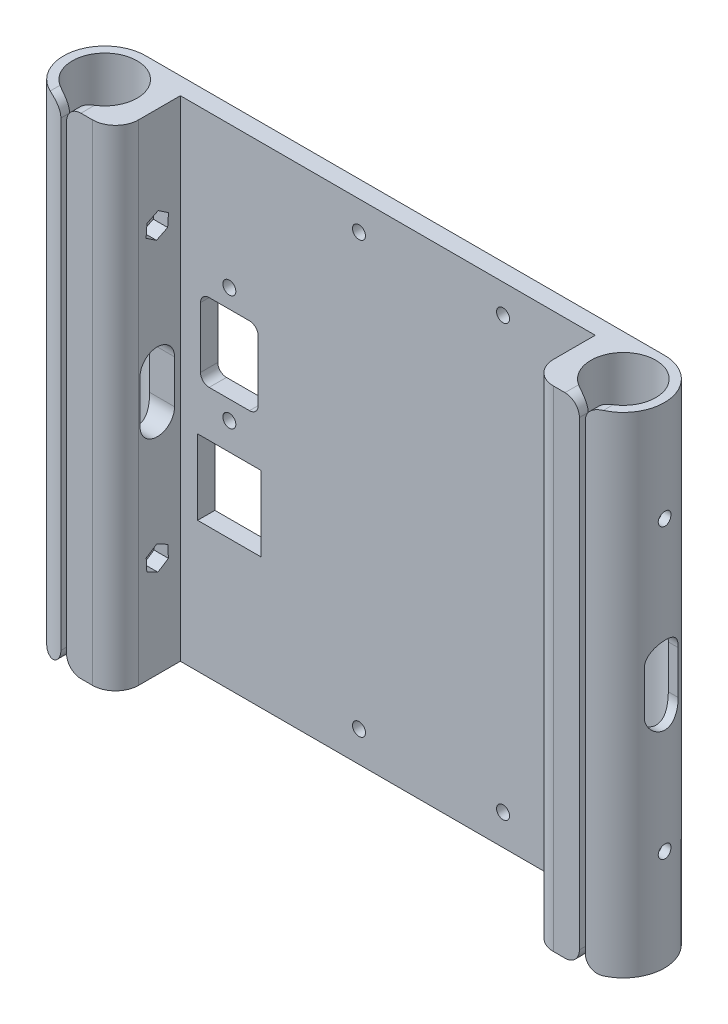
SolidWorks part; units mm, degrees
ref_plane "Front Plane" through (0, 0, 0) normal (0, 0, 1) x (1, 0, 0)
ref_plane "Top Plane" through (0, 0, 0) normal (0, 1, 0) x (1, 0, 0)
ref_plane "Right Plane" through (0, 0, 0) normal (1, 0, 0) x (0, 0, -1)
sketch "Sketch1" plane through (0, 0, 0) normal (0, 1, 0) x (1, 0, 0)
  line L0 (137.4606, -14.5) -> (119.4606, -14.5)
  line L1 (119.4606, -14.5) -> (119.4606, 8)
  line L2 (-42.5394, -14.5) -> (-24.5394, -14.5)
  line L3 (-42.5394, 14) -> (137.4606, 14)
  line L4 (119.4606, 8) -> (-24.5394, 8)
  line L5 (-24.5394, -14.5) -> (-24.5394, 8)
  circle A0 centre (-42.5394, -0.25) radius 11.25
  circle A1 centre (137.4606, -0.25) radius 11.25
  arc A2 (-42.5394, -14.5) -> (-42.5394, 14) centre (-42.5394, -0.25) cw
  arc A6 (137.4606, 14) -> (137.4606, -14.5) centre (137.4606, -0.25) cw
  dimension "D3" = 22.5
  dimension "D4" = 22.5
  dimension "D5" = 180
  dimension "D6" = 3
  dimension "D1" = 18
  dimension "D2" = 18
  dimension "D8" = 6
extrude "Boss-Extrude1" add sketch "Sketch1" along normal blind 170
fillet "Fillet1" radius 8 2 edges at (119.4606, 85, 14.5) (-24.5394, 85, 14.5)
sketch "Sketch2" plane through (0, 0, -8) normal (0, 0, 1) x (1, 0, 0)
  line L0 (119.4606, 160) -> (87.4606, 160) construction
  line L1 (119.4606, 170) -> (119.4606, 0) construction
  line L2 (87.4606, 160) -> (37.4606, 160) construction
  line L4 (137.4606, 170) -> (-42.5394, 170) construction
  circle A0 centre (87.4606, 160) radius 2.25
  circle A1 centre (37.4606, 160) radius 2.25
  circle A2 centre (37.4606, 10.6363) radius 2.25
  circle A3 centre (87.4606, 10.6363) radius 2.25
  dimension "D4" = 4.5
  dimension "D5" = 4.5
  dimension "D6" = 4.5
  dimension "D1" = 32
  dimension "D2" = 50
  dimension "D3" = 10
extrude "Cut-Extrude1" cut sketch "Sketch2" against normal blind 10
sketch "Sketch3" plane through (0, 0, -8) normal (0, 0, 1) x (1, 0, 0)
  line L1 (2.4606, 87.3248) -> (-17.5394, 87.3248)
  line L2 (2.4606, 87.3248) -> (2.4606, 114.3248)
  line L3 (2.4606, 114.3248) -> (-17.5394, 114.3248)
  line L4 (-17.5394, 87.3248) -> (-17.5394, 114.3248)
  line L6 (-7.5394, 120.8248) -> (-7.5394, 114.3248) construction
  line L7 (-7.5394, 114.3248) -> (-7.5394, 80.8248) construction
  circle A0 centre (37.4606, 160) radius 2.25 construction
  circle A1 centre (-7.5394, 80.8248) radius 2.25
  circle A2 centre (-7.5394, 120.8248) radius 2.25
  point P6 (-7.5394, 87.3248)
  point P13 (2.4606, 100.8248)
  dimension "D5" = 4.5
  dimension "D6" = 4.5
  dimension "D1" = 20
  dimension "D2" = 27
  dimension "D3" = 45
  dimension "D4" = 6.5
  dimension "D7" = 40
  dimension "D8" = 20
extrude "Cut-Extrude2" cut sketch "Sketch3" against normal blind 10
fillet "Fillet2" radius 3 4 edges at (-17.5394, 87.3248, -11) (-17.5394, 114.3248, -11) (2.4606, 114.3248, -11) (2.4606, 87.3248, -11)
sketch "Sketch4" plane through (0, 0, -14) normal (0, 0, -1) x (-1, 0, 0)
  line L0 (7.5394, 80.8248) -> (7.5394, 0) construction
  line L1 (-137.4606, 0) -> (42.5394, 0) construction
  line L3 (18.5394, 45.3658) -> (-3.4606, 45.3658)
  line L4 (18.5394, 45.3658) -> (18.5394, 71.3658)
  line L5 (18.5394, 71.3658) -> (-3.4606, 71.3658)
  line L6 (-3.4606, 45.3658) -> (-3.4606, 71.3658)
  line L7 (18.5394, 45.3658) -> (-3.4606, 71.3658) construction
  line L8 (18.5394, 71.3658) -> (-3.4606, 45.3658) construction
  point P5 (7.5394, 58.3658)
  dimension "D1" = 22
  dimension "D2" = 26
extrude "Cut-Extrude3" cut sketch "Sketch4" against normal blind 10
sketch "Sketch5" plane through (0, 0, 14.5) normal (0, 0, 1) x (1, 0, 0)
  line L0 (-42.5394, 170) -> (-42.5394, 0)
  line L1 (137.4606, 170) -> (137.4606, 0)
extrude "Cut-Extrude-Thin1" cut sketch "Sketch5" against normal blind 10 thin thin type mid plane wall 2
fillet "Fillet3" radius 5 8 edges at (138.4606, 0, 12.9602) (136.4606, 0, 12.9777) (138.4606, 170, 12.9602) (136.4606, 170, 12.9777) (-41.5394, 170, 12.9777) (-43.5394, 170, 12.9602) (-43.5394, 0, 12.9602) (-41.5394, 0, 12.9777)
sketch "Sketch7" plane through (-24.5394, 0, 0) normal (1, 0, 0) x (0, 0, -1)
  line L0 (0, 170) -> (0, 0) construction
  line L1 (-6.5, 170) -> (8, 170) construction
  line L2 (-6.5, 0) -> (8, 0) construction
  line L4 (0, 92.5) -> (0, 77.5) construction
  line L5 (6, 92.5) -> (6, 77.5)
  line L6 (-6, 92.5) -> (-6, 77.5)
  arc A0 (6, 92.5) -> (-6, 92.5) centre (0, 92.5) ccw
  arc A1 (-6, 77.5) -> (6, 77.5) centre (0, 77.5) ccw
  circle A2 centre (0, 135) radius 2.25
  circle A3 centre (0, 35) radius 2.25
  point P9 (0, 85)
  dimension "D3" = 6
  dimension "D6" = 4.5
  dimension "D7" = 4.5
  dimension "D1" = 11
  dimension "D2" = 15
  dimension "D4" = 50
  dimension "D5" = 50
extrude "Cut-Extrude4" cut sketch "Sketch7" against normal through all both and the other way through all
sketch "Sketch8" plane through (-24.5394, 0, 0) normal (1, 0, 0) x (0, 0, -1)
  line L1 (-0.2893, 130.6795) -> (3.597, 132.5892)
  line L2 (3.597, 132.5892) -> (3.8863, 136.9097)
  line L3 (3.8863, 136.9097) -> (0.2893, 139.3205)
  line L4 (0.2893, 139.3205) -> (-3.597, 137.4108)
  line L5 (-3.597, 137.4108) -> (-3.8863, 133.0903)
  line L6 (-3.8863, 133.0903) -> (-0.2893, 130.6795)
  line L7 (-0.208, 39.3251) -> (-3.8497, 36.9824)
  line L8 (-3.8497, 36.9824) -> (-3.6417, 32.6573)
  line L9 (-3.6417, 32.6573) -> (0.208, 30.6749)
  line L10 (0.208, 30.6749) -> (3.8497, 33.0176)
  line L11 (3.8497, 33.0176) -> (3.6417, 37.3427)
  line L12 (3.6417, 37.3427) -> (-0.208, 39.3251)
  circle A0 centre (0, 135) radius 3.75 construction
  circle A1 centre (0, 35) radius 3.75 construction
  dimension "D1" = 7.5
extrude "Cut-Extrude5" cut sketch "Sketch8" against normal blind 5
ref_plane "Plane1" through (47.4606, 0, 0) normal (1, 0, 0) x (0, 0, -1)
mirror "Mirror1" about plane through (47.4606, 0, 0) normal (1, 0, 0) of "Cut-Extrude5"
sketch "Sketch9" plane through (0, 0, -14) normal (0, 0, -1) x (-1, 0, 0)
  line L0 (42.5394, 85) -> (-137.4606, 85) construction
  line L1 (42.5394, 170) -> (42.5394, 0) construction
  line L2 (-137.4606, 170) -> (-137.4606, 0) construction
  line L3 (-137.4606, 0) -> (42.5394, 0) construction
  line L4 (7.5394, 15) -> (-102.4606, 15)
  line L5 (17.5394, 25) -> (17.5394, 30)
  line L6 (7.5394, 155) -> (-102.4606, 155)
  line L7 (-112.4606, 25) -> (-112.4606, 145)
  line L8 (17.5394, 15) -> (-112.4606, 155) construction
  line L9 (17.5394, 155) -> (-112.4606, 15) construction
  line L10 (7.5394, 40) -> (-2.4606, 40)
  line L11 (-12.4606, 50) -> (-12.4606, 120)
  line L12 (-2.4606, 130) -> (7.5394, 130)
  line L13 (17.5394, 140) -> (17.5394, 145)
  line L14 (-2.4606, 90.3248) -> (-2.4606, 111.3248) construction
  arc A0 (-12.4606, 120) -> (-2.4606, 130) centre (-2.4606, 120) cw
  arc A1 (-2.4606, 40) -> (-12.4606, 50) centre (-2.4606, 50) cw
  arc A2 (17.5394, 145) -> (7.5394, 155) centre (7.5394, 145) ccw
  arc A3 (-102.4606, 155) -> (-112.4606, 145) centre (-102.4606, 145) ccw
  arc A4 (-102.4606, 15) -> (-112.4606, 25) centre (-102.4606, 25) cw
  arc A5 (7.5394, 15) -> (17.5394, 25) centre (7.5394, 25) ccw
  arc A6 (7.5394, 130) -> (17.5394, 140) centre (7.5394, 140) ccw
  arc A7 (7.5394, 40) -> (17.5394, 30) centre (7.5394, 30) cw
  point P6 (-47.4606, 85)
  point P37 (17.5394, 130)
  dimension "D4" = 10
  dimension "D6" = 10
  dimension "D1" = 130
  dimension "D2" = 15
  dimension "D3" = 10
  dimension "D5" = 15
extrude "Cut-Extrude6" cut sketch "Sketch9" against normal blind 3
sketch "Sketch10" plane through (0, 0, -11) normal (0, 0, -1) x (-1, 0, 0)
  line L1 (-74.7646, 20.5156) -> (-104.7646, 20.5156)
  line L2 (-74.7646, 20.5156) -> (-74.7646, 148.6168)
  line L3 (-74.7646, 148.6168) -> (-104.7646, 148.6168)
  line L4 (-104.7646, 20.5156) -> (-104.7646, 148.6168)
  line L5 (-38.8219, 20.5156) -> (-68.8219, 20.5156)
  line L6 (-38.8219, 20.5156) -> (-38.8219, 148.6168)
  line L7 (-38.8219, 148.6168) -> (-68.8219, 148.6168)
  line L8 (-68.8219, 20.5156) -> (-68.8219, 148.6168)
  line L9 (-3.8229, 20.5156) -> (-33.8229, 20.5156)
  line L10 (-3.8229, 20.5156) -> (-3.8229, 34.5156)
  line L11 (-3.8229, 34.5156) -> (-33.8229, 34.5156)
  line L12 (-33.8229, 20.5156) -> (-33.8229, 34.5156)
  line L13 (-33.8229, 135.8002) -> (-3.8229, 135.8002)
  line L14 (-33.8229, 135.8002) -> (-33.8229, 149.8002)
  line L15 (-33.8229, 149.8002) -> (-3.8229, 149.8002)
  line L16 (-3.8229, 135.8002) -> (-3.8229, 149.8002)
  line L17 (-33.8229, 42.389) -> (-18.8229, 42.389)
  line L18 (-33.8229, 42.389) -> (-33.8229, 130.09)
  line L19 (-33.8229, 130.09) -> (-18.8229, 130.09)
  line L20 (-18.8229, 42.389) -> (-18.8229, 130.09)
  dimension "D1" = 30
  dimension "D2" = 30
  dimension "D3" = 30
  dimension "D4" = 14
  dimension "D5" = 14
  dimension "D6" = 30
  dimension "D7" = 15
extrude "Cut-Extrude7" cut sketch "Sketch10" against normal blind 2
